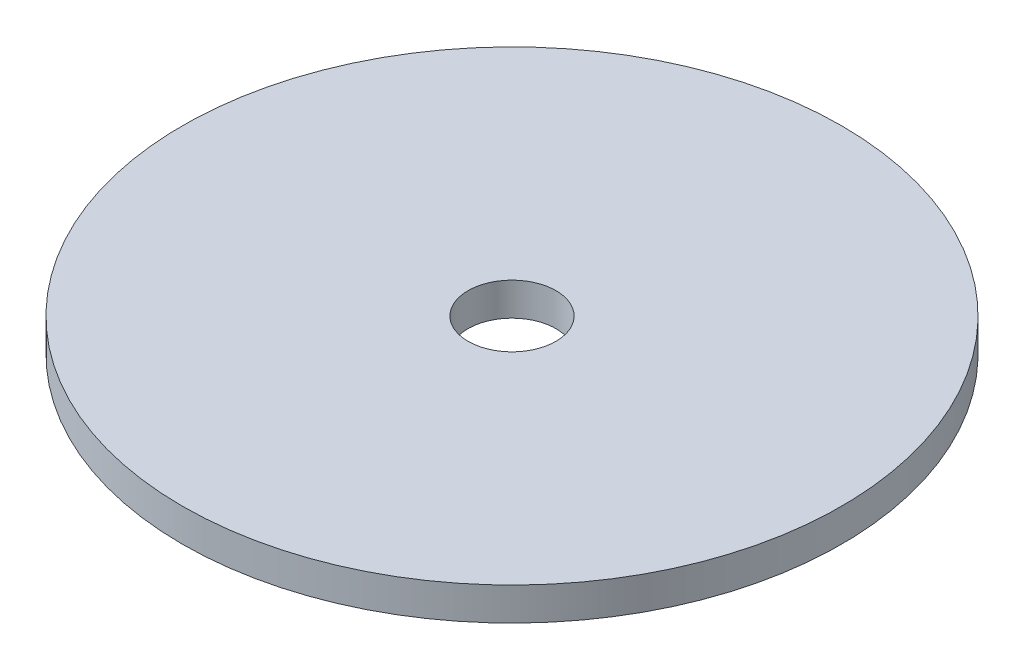
SolidWorks part; units mm, degrees
ref_plane "Plan de face" through (0, 0, 0) normal (0, 0, 1) x (1, 0, 0)
ref_plane "Plan de dessus" through (0, 0, 0) normal (0, 1, 0) x (1, 0, 0)
ref_plane "Plan de droite" through (0, 0, 0) normal (1, 0, 0) x (0, 0, -1)
sketch "Esquisse1" plane through (0, 0, 0) normal (0, 1, 0) x (1, 0, 0)
  circle A1 centre (0, 0) radius 30
  circle A3 centre (0, 0) radius 4
  point P15 (18.887, 5.7743)
  dimension "D2" = 60
  dimension "D1" = 8
extrude "Boss.-Extru.1" add sketch "Esquisse1" along normal blind 3
